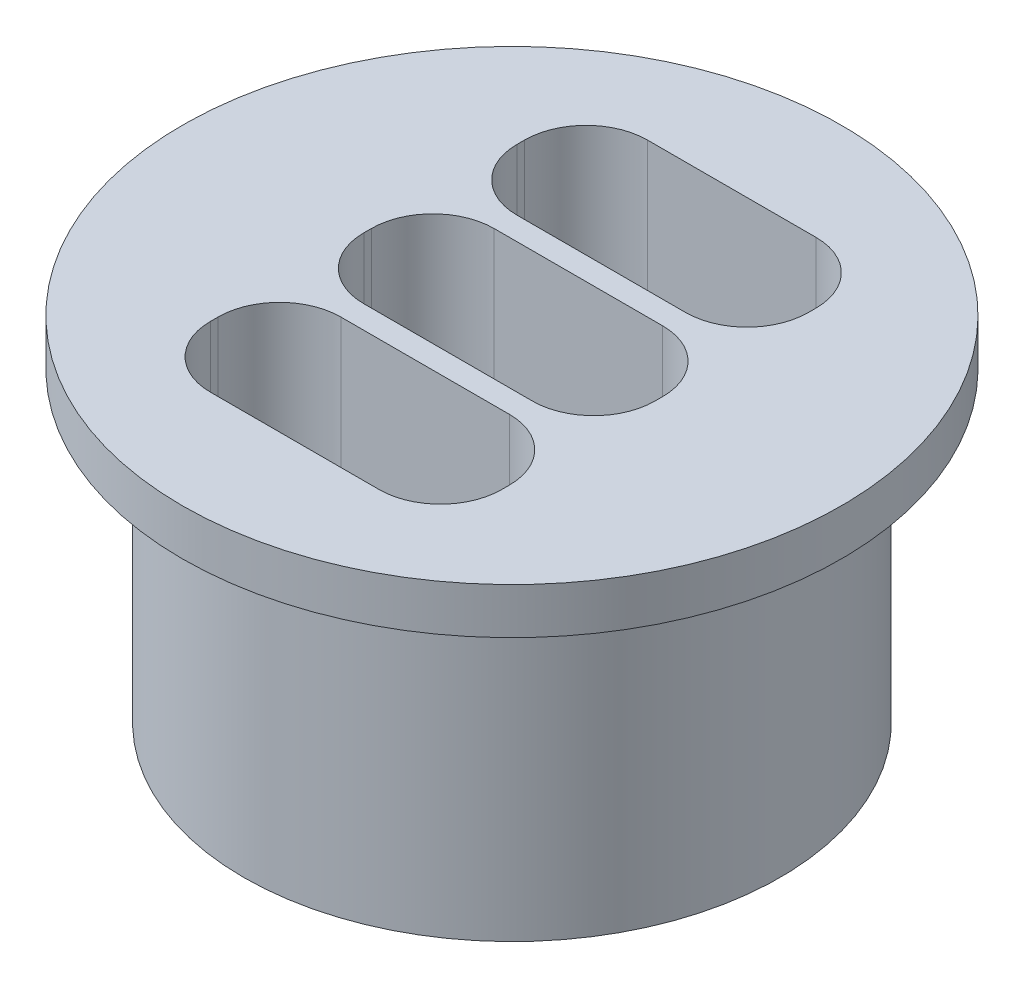
SolidWorks part; units mm, degrees
ref_plane "Front Plane" through (0, 0, 0) normal (0, 0, 1) x (1, 0, 0)
ref_plane "Top Plane" through (0, 0, 0) normal (0, 1, 0) x (1, 0, 0)
ref_plane "Right Plane" through (0, 0, 0) normal (1, 0, 0) x (0, 0, -1)
sketch "Sketch1" plane through (0, 0, 0) normal (0, 1, 0) x (1, 0, 0)
  circle A0 centre (0, 0) radius 17.5
  dimension "D1" = 35
extrude "Boss-Extrude1" add sketch "Sketch1" along normal blind 20
sketch "Sketch2" plane through (0, 20, 0) normal (0, 1, 0) x (1, 0, 0)
  circle A0 centre (0, 0) radius 21.5
  dimension "D1" = 43
extrude "Boss-Extrude2" add sketch "Sketch2" along normal blind 3
sketch "Sketch3" plane through (0, 23, 0) normal (0, 1, 0) x (1, 0, 0)
  line L0 (0, 16.1651) -> (0, -18.7714) construction
  line L1 (-9.5, 4.3338) -> (-9.5, -4.1662)
  line L2 (-9.5, 14.3338) -> (9.5, 14.3338)
  line L3 (-9.5, 14.3338) -> (-9.5, 5.8338)
  line L4 (-9.5, 5.8338) -> (9.5, 5.8338)
  line L5 (9.5, 14.3338) -> (9.5, 5.8338)
  line L6 (-9.5, 14.3338) -> (9.5, 5.8338) construction
  line L7 (-9.5, 5.8338) -> (9.5, 14.3338) construction
  line L8 (-9.5, 4.3338) -> (9.5, 4.3338)
  line L9 (9.5, 4.3338) -> (9.5, -4.1662)
  line L10 (-9.5, -4.1662) -> (9.5, -4.1662)
  line L11 (-9.5, -5.6662) -> (-9.5, -14.1662)
  line L12 (-9.5, -5.6662) -> (9.5, -5.6662)
  line L13 (9.5, -5.6662) -> (9.5, -14.1662)
  line L14 (-9.5, -14.1662) -> (9.5, -14.1662)
  point P3 (0, 10.0838)
  dimension "D1" = 19
  dimension "D2" = 8.5
  dimension "D3" = 3
extrude "Cut-Extrude3" cut sketch "Sketch3" against normal blind 23
fillet "Fillet11" radius 4 8 edges at (9.5, 11.5, 5.6662) (-9.5, 11.5, 14.1662) (-9.5, 11.5, 5.6662) (9.5, 11.5, 14.1662) (9.5, 11.5, 4.1662) (-9.5, 11.5, 4.1662) (-9.5, 11.5, -4.3338) (9.5, 11.5, -4.3338)
fillet "Fillet12" radius 4 4 edges at (-9.5, 11.5, -14.3338) (9.5, 11.5, -5.8338) (-9.5, 11.5, -5.8338) (9.5, 11.5, -14.3338)
